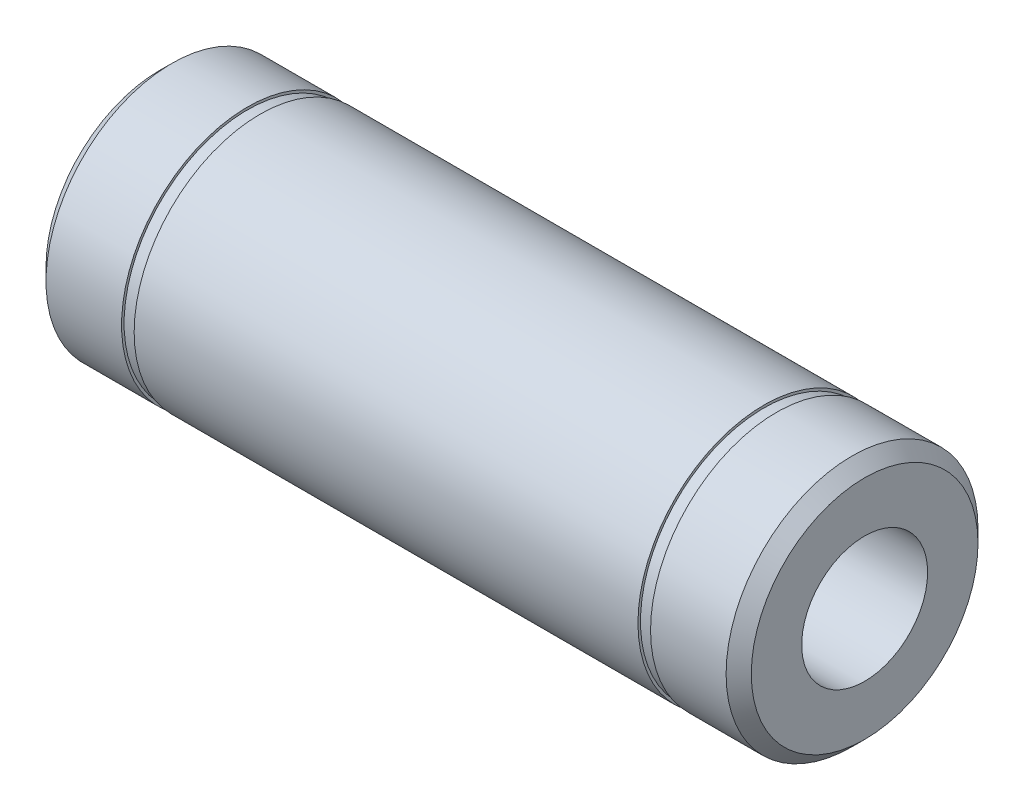
SolidWorks part; units mm, degrees
ref_plane "前视基准面" through (0, 0, 0) normal (0, 0, 1) x (1, 0, 0)
ref_plane "上视基准面" through (0, 0, 0) normal (0, 1, 0) x (1, 0, 0)
ref_plane "右视基准面" through (0, 0, 0) normal (1, 0, 0) x (0, 0, -1)
sketch "草图1" plane through (0, 0, 0) normal (1, 0, 0) x (0, 0, -1)
  circle A0 centre (0, 0) radius 5
  circle A1 centre (0, 0) radius 2.5
  dimension "D1" = 5
  dimension "D2" = 10
extrude "凸台-拉伸1" add sketch "草图1" along normal mid plane 28
chamfer "倒角1" distance 0.5 angle 45 2 edges at (14, 0, -5) (-14, 0, -5)
sketch "草图3" plane through (0, 0, 0) normal (1, 0, 0) x (0, 0, -1)
  circle A2 centre (0, 0) radius 4.9
  circle A3 centre (0, 0) radius 4.9
  dimension "D1" = 0.1
extrude "切除-拉伸1" cut sketch "草图3" against normal blind 0.5 from offset 10 flip side to cut offset against normal yes
mirror "镜向1" about plane through (0, 0, 0) normal (1, 0, 0) of "切除-拉伸1"
